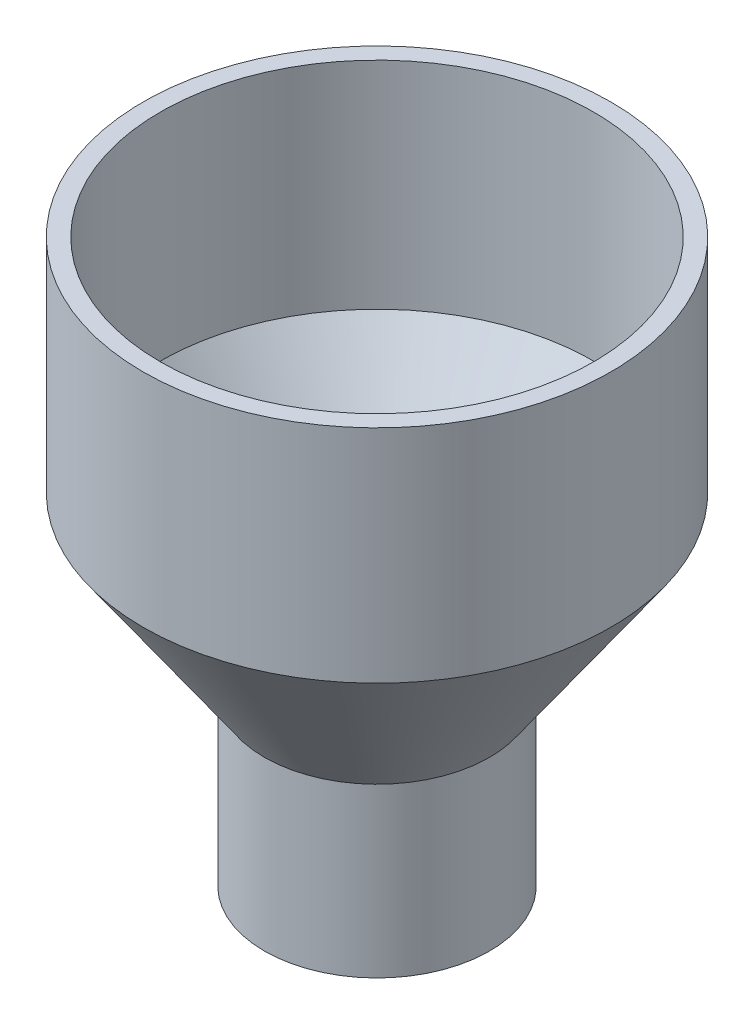
SolidWorks part; units mm, degrees
ref_plane "Plano frontal" through (0, 0, 0) normal (0, 0, 1) x (1, 0, 0)
ref_plane "Plano superior" through (0, 0, 0) normal (0, 1, 0) x (1, 0, 0)
ref_plane "Plano direito" through (0, 0, 0) normal (1, 0, 0) x (0, 0, -1)
sketch "Esboço1" plane through (0, 0, 0) normal (0, 0, 1) x (1, 0, 0)
  line L0 (-25, 64.9051) -> (-23.6784, 64.9051)
  line L1 (-11, 0) -> (-11, 20)
  line L4 (-25, 40) -> (-11, 20)
  line L5 (-25, 40) -> (-25, 64.9051)
  line L6 (-27, 64.9051) -> (-25, 64.9051)
  line L7 (0, 64.9051) -> (0, 1.1441) construction
  line L8 (-13, 0) -> (-13, 19.3696)
  line L9 (-27, 39.3696) -> (-13, 19.3696)
  line L10 (-27, 39.3696) -> (-27, 64.9051)
  line L11 (-25, 64.9051) -> (-27, 64.9051)
  line L12 (-27, 66.9051) -> (0, 66.9051) construction
  line L13 (-11, 0) -> (-13, 0)
  line L14 (-27, 39.3696) -> (-27, 66.9051) construction
  line L15 (-13, -2) -> (-13, 19.3696) construction
  line L16 (0, -2) -> (-13, -2) construction
  line L17 (-25, 64.9051) -> (0, 64.9051) construction
  line L18 (0, 0) -> (-11, 0) construction
  line L19 (0, 64.9051) -> (-24.3392, 64.9051)
  line L20 (-11, 0) -> (0, 0)
  line L21 (0, 0) -> (0, 2.3359)
  line L22 (0, 2.3359) -> (0, 0)
  dimension "D1" = 11
  dimension "D2" = 2
  dimension "D3" = 25
  dimension "D4" = 2
  dimension "D5" = 145.008
  dimension "D6" = 34.992
  dimension "D7" = 39.3696
  dimension "D8" = 64.9051
revolve "Revolução2" add sketch "Esboço1" angle 360 about L7
